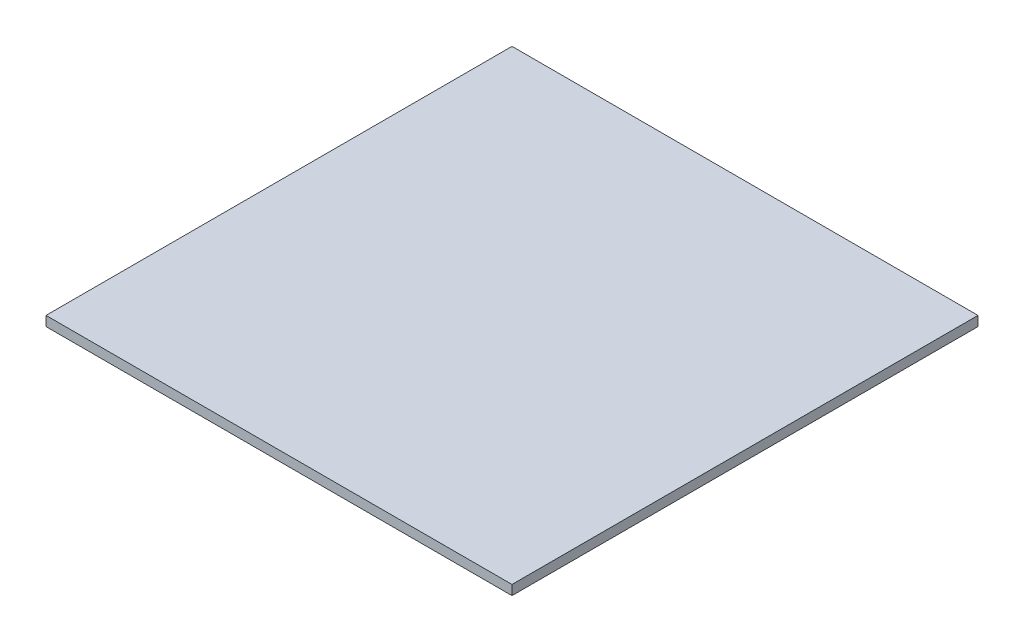
SolidWorks part; units mm, degrees
ref_plane "Front Plane" through (0, 0, 0) normal (0, 0, 1) x (1, 0, 0)
ref_plane "Top Plane" through (0, 0, 0) normal (0, 1, 0) x (1, 0, 0)
ref_plane "Right Plane" through (0, 0, 0) normal (1, 0, 0) x (0, 0, -1)
sketch "Sketch1" plane through (0, 0, 0) normal (0, 1, 0) x (1, 0, 0)
  line L1 (-304.8, -304.8) -> (304.8, -304.8)
  line L2 (-304.8, -304.8) -> (-304.8, 304.8)
  line L3 (-304.8, 304.8) -> (304.8, 304.8)
  line L4 (304.8, -304.8) -> (304.8, 304.8)
  line L5 (-304.8, -304.8) -> (304.8, 304.8) construction
  line L6 (-304.8, 304.8) -> (304.8, -304.8) construction
  point P0 (0, 0)
  dimension "D1" = 609.6
  dimension "D2" = 609.6
extrude "Boss-Extrude1" add sketch "Sketch1" along normal mid plane 12.7
